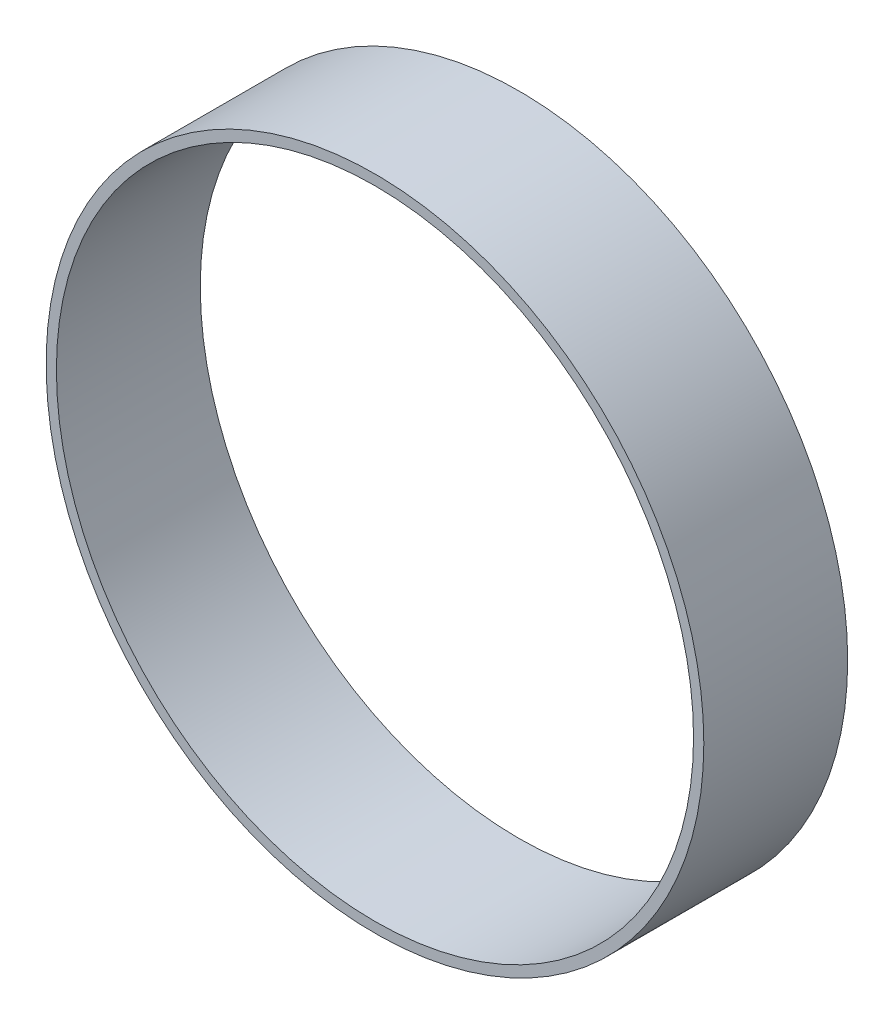
SolidWorks part; units mm, degrees
material "Plain Carbon Steel"
ref_plane "Front Plane" through (0, 0, 0) normal (0, 0, 1) x (1, 0, 0)
ref_plane "Top Plane" through (0, 0, 0) normal (0, 1, 0) x (1, 0, 0)
ref_plane "Right Plane" through (0, 0, 0) normal (1, 0, 0) x (0, 0, -1)
sketch "Sketch1" plane through (0, 0, 0) normal (0, 0, 1) x (1, 0, 0)
  circle A0 centre (0, 0) radius 50.8
  circle A1 centre (0, 0) radius 49.2125
  dimension "D1" = 101.6
  dimension "D2" = 98.425
extrude "Boss-Extrude1" add sketch "Sketch1" along normal blind 22.225
